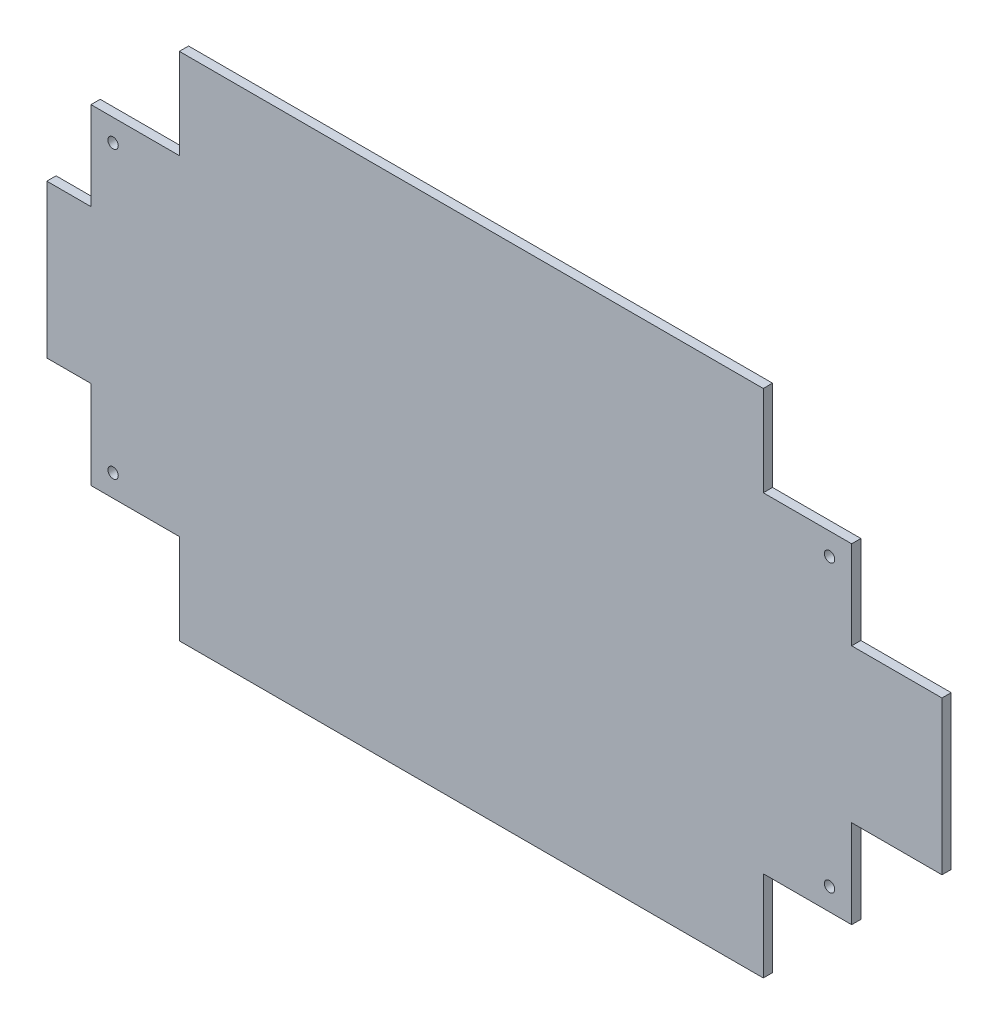
SolidWorks part; units mm, degrees
material "Pin"
ref_plane "Plan de face" through (0, 0, 0) normal (0, 0, 1) x (1, 0, 0)
ref_plane "Plan de dessus" through (0, 0, 0) normal (0, 1, 0) x (1, 0, 0)
ref_plane "Plan de droite" through (0, 0, 0) normal (1, 0, 0) x (0, 0, -1)
sketch "Esquisse1" plane through (0, 0, 0) normal (0, 0, 1) x (1, 0, 0)
  line L0 (-615.95, 52.7) -> (-615.95, -52.7)
  line L1 (-615.95, -52.7) -> (-553.8, -52.7)
  line L2 (-553.8, -52.7) -> (-553.8, -113.5)
  line L3 (-553.8, -113.5) -> (-493, -113.5)
  line L4 (-493, -113.5) -> (-493, -174.3)
  line L5 (-493, -174.3) -> (-91.2, -174.3)
  line L6 (-91.2, -174.3) -> (-91.2, -113.5)
  line L7 (-91.2, -113.5) -> (-30.4, -113.5)
  line L8 (-30.4, -113.5) -> (-30.4, -52.7)
  line L9 (-30.4, -52.7) -> (0, -52.7)
  line L10 (0, -52.7) -> (0, 52.7)
  line L11 (0, 52.7) -> (-30.4, 52.7)
  line L12 (-30.4, 52.7) -> (-30.4, 113.5)
  line L13 (-30.4, 113.5) -> (-91.2, 113.5)
  line L14 (-91.2, 113.5) -> (-91.2, 182)
  line L15 (-615.95, 52.7) -> (-553.8, 52.7)
  line L16 (-553.8, 52.7) -> (-553.8, 113.5)
  line L17 (-553.8, 113.5) -> (-493, 113.5)
  line L18 (-493, 113.5) -> (-493, 182)
  line L19 (-493, 182) -> (-91.2, 182)
  point P28 (0, 0)
  dimension "D1" = 105.4
  dimension "D2" = 401.8
  dimension "D3" = 60.8
  dimension "D4" = 30.4
  dimension "D5" = 60.8
  dimension "D6" = 68.5
  dimension "D7" = 60.8
  dimension "D8" = 60.8
  dimension "D9" = 62.15
extrude "Boss.-Extru.1" add sketch "Esquisse1" along normal blind 6.35
sketch "Esquisse2" plane through (0, 0, 6.35) normal (0, 0, 1) x (1, 0, 0)
  line L0 (-91.2, 113.5) -> (-91.2, 182) construction
  line L1 (-493, 182) -> (-91.2, 182)
  line L2 (-493, 182) -> (-493, 175.65)
  line L3 (-493, 175.65) -> (-91.2, 175.65)
  line L4 (-91.2, 182) -> (-91.2, 175.65)
  line L5 (-493, 182) -> (-91.2, 175.65) construction
  line L6 (-493, 175.65) -> (-91.2, 182) construction
  line L7 (-91.2, 182) -> (-493, 182) construction
  line L8 (-493, 182) -> (-493, 113.5) construction
  point P4 (-292.1, 178.825)
  dimension "D1" = 6.35
extrude "Enlèv. mat.-Extru.1" cut sketch "Esquisse2" against normal through all
hole_wizard "Dégagement 1/41" positions "Esquisse3" profile "Esquisse4" hole size "1/4" standard "Ansi Inch" end condition through all
sketch "Esquisse3" plane through (0, 0, 0) normal (0, 0, -1) x (-1, 0, 0)
  point P0 (45.6, 98.3)
  point P2 (45.6, -98.3)
  point P4 (538.6, -98.3)
  point P6 (538.6, 98.3)
sketch "Esquisse4" plane through (-45.6, 98.3, 0) normal (1, 0, 0) x (0, 1, 0)
  line L0 (0, 0) -> (0, 6.35)
  line L1 (0, 6.35) -> (3.5712, 6.35)
  line L2 (3.5712, 6.35) -> (3.5712, 0)
  line L5 (3.5712, 0) -> (0, 0)
  line L11 (0, -6.35) -> (0, 107.95) construction
  dimension "Diamètre du perçage jusqu'au prochain" = 7.1425
  dimension "Profondeur du perçage jusqu'au prochain" = 6.35
sketch "Esquisse5" plane through (0, 0, 6.35) normal (0, 0, 1) x (1, 0, 0)
  line L0 (-91.2, -174.3) -> (-91.2, -113.5) construction
  line L1 (-493, -174.3) -> (-91.2, -174.3)
  line L2 (-493, -174.3) -> (-493, -175.65)
  line L3 (-493, -175.65) -> (-91.2, -175.65)
  line L4 (-91.2, -174.3) -> (-91.2, -175.65)
  line L5 (-493, -174.3) -> (-91.2, -175.65) construction
  line L6 (-493, -175.65) -> (-91.2, -174.3) construction
  point P4 (-292.1, -174.975)
  dimension "D1" = 1.35
extrude "Boss.-Extru.2" add sketch "Esquisse5" against normal through all
mirror "Symétrie1" about plane through (0, -52.7, 6.35) normal (-1, 0, 0) of bodies 105 102
delete or keep bodies "Corps-Supprimer/Garder 1" type delete bodies bodies 105
